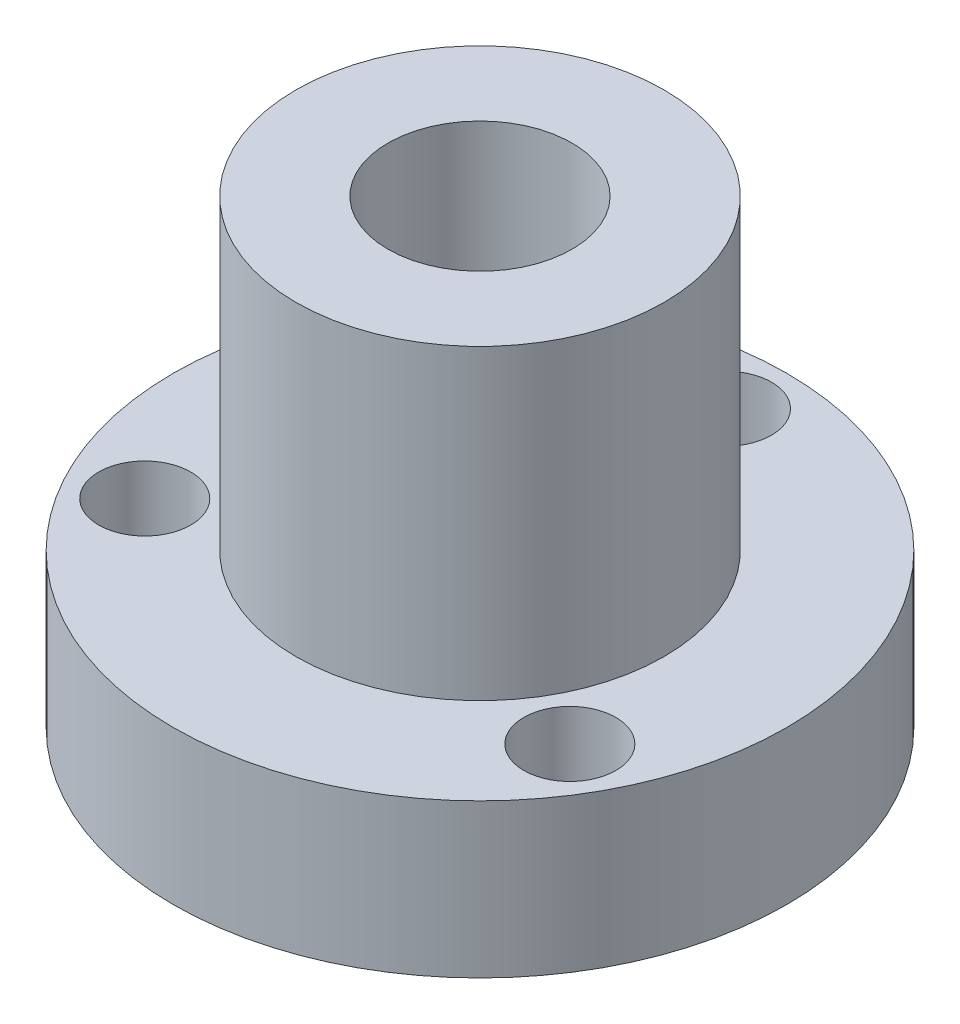
SolidWorks part; units mm, degrees
ref_plane "Front Plane" through (0, 0, 0) normal (0, 0, 1) x (1, 0, 0)
ref_plane "Top Plane" through (0, 0, 0) normal (0, 1, 0) x (1, 0, 0)
ref_plane "Right Plane" through (0, 0, 0) normal (1, 0, 0) x (0, 0, -1)
sketch "Sketch1" plane through (0, 0, 0) normal (0, 1, 0) x (1, 0, 0)
  circle A0 centre (0, 0) radius 10
  dimension "D1" = 20
extrude "Boss-Extrude1" add sketch "Sketch1" along normal blind 5
sketch "Sketch2" plane through (0, 5, 0) normal (0, 1, 0) x (1, 0, 0)
  circle A0 centre (0, 0) radius 6
  dimension "D1" = 12
extrude "Boss-Extrude2" add sketch "Sketch2" along normal blind 10
sketch "Sketch3" plane through (0, 15, 0) normal (0, 1, 0) x (1, 0, 0)
  circle A0 centre (0, 0) radius 3
  dimension "D1" = 6
extrude "Cut-Extrude1" cut sketch "Sketch3" against normal through all
sketch "Sketch4" plane through (0, 5, 0) normal (0, 1, 0) x (1, 0, 0)
  circle A0 centre (0, 8) radius 1.5
  circle A1 centre (6.9282, -4) radius 1.5
  circle A2 centre (-6.9282, -4) radius 1.5
  point P9 (0, 0)
  dimension "D1" = 3
  dimension "D2" = 8
  dimension "D3" = 3
extrude "Cut-Extrude2" cut sketch "Sketch4" against normal through all
